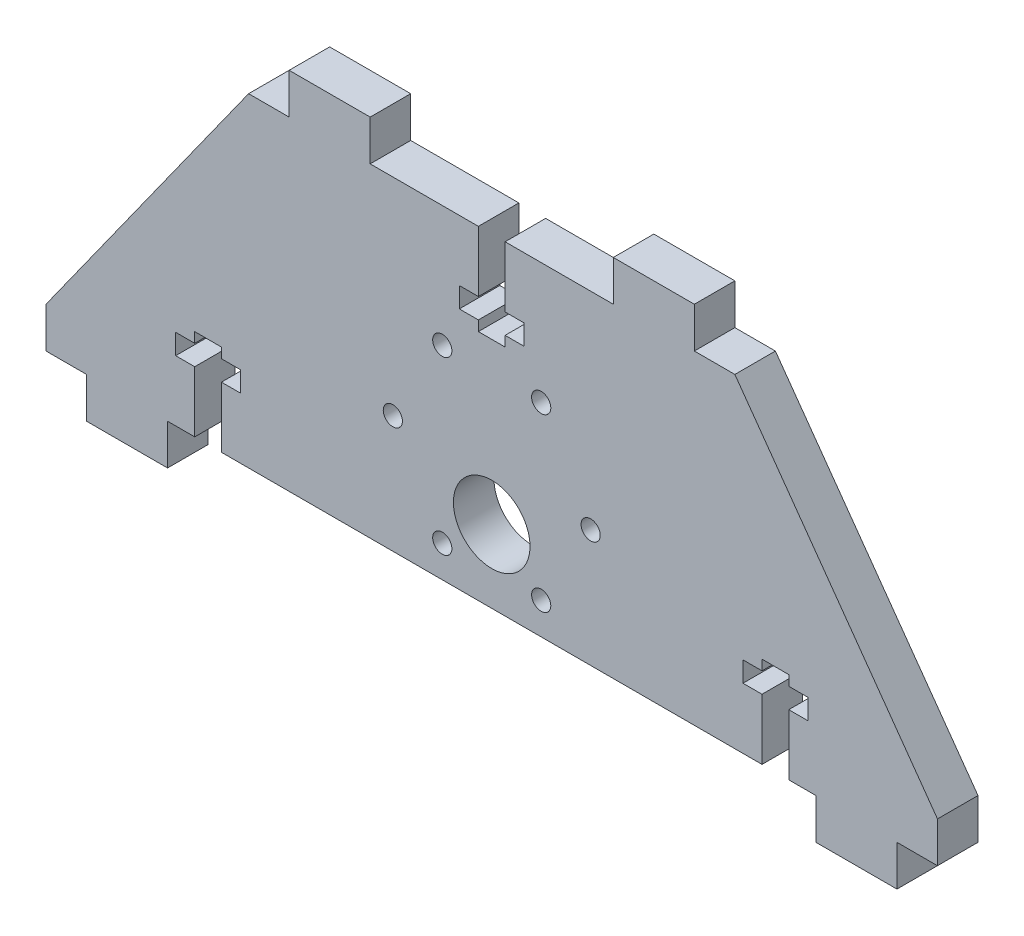
SolidWorks part; units mm, degrees
ref_plane "Front Plane" through (0, 0, 0) normal (0, 0, 1) x (1, 0, 0)
ref_plane "Top Plane" through (0, 0, 0) normal (0, 1, 0) x (1, 0, 0)
ref_plane "Right Plane" through (0, 0, 0) normal (1, 0, 0) x (0, 0, -1)
sketch "Sketch1" plane through (0, 0, 0) normal (0, 0, 1) x (1, 0, 0)
  line L1 (-69.85, 25.4) -> (69.85, 25.4)
  line L2 (-69.85, 25.4) -> (-69.85, -25.4)
  line L3 (-69.85, -25.4) -> (69.85, -25.4)
  line L4 (69.85, 25.4) -> (69.85, -25.4)
  line L5 (-69.85, 25.4) -> (69.85, -25.4) construction
  line L6 (-69.85, -25.4) -> (69.85, 25.4) construction
  point P0 (0, 0)
  dimension "D1" = 50.8
  dimension "D2" = 139.7
extrude "Boss-Extrude1" add sketch "Sketch1" along normal blind 6.35
sketch "Sketch2" plane through (0, 0, 0) normal (0, 0, -1) x (-1, 0, 0)
  line L0 (69.85, -25.4) -> (-69.85, -25.4) construction
  line L1 (-63.5, -25.4) -> (-50.8, -25.4)
  line L2 (-63.5, -25.4) -> (-63.5, -31.75)
  line L3 (-63.5, -31.75) -> (-50.8, -31.75)
  line L4 (-50.8, -25.4) -> (-50.8, -31.75)
  line L5 (-69.85, -25.4) -> (-69.85, 25.4) construction
  line L6 (-69.85, 25.4) -> (69.85, 25.4) construction
  line L7 (-31.75, 25.4) -> (-19.05, 25.4)
  line L8 (-31.75, 25.4) -> (-31.75, 31.75)
  line L9 (-31.75, 31.75) -> (-19.05, 31.75)
  line L10 (-19.05, 25.4) -> (-19.05, 31.75)
  dimension "D1" = 6.35
  dimension "D2" = 12.7
  dimension "D3" = 6.35
  dimension "D4" = 6.35
  dimension "D5" = 12.7
  dimension "D6" = 38.1
extrude "Boss-Extrude2" add sketch "Sketch2" against normal blind 6.35
sketch "Sketch3" plane through (0, 0, 0) normal (0, 0, -1) x (-1, 0, 0)
  line L1 (-46.5455, -25.4) -> (-46.5455, -15.875)
  line L2 (69.85, -25.4) -> (-50.8, -25.4) construction
  line L3 (-46.5455, -15.875) -> (-49.53, -15.875)
  line L4 (-49.53, -15.875) -> (-49.53, -12.7)
  line L5 (-49.53, -12.7) -> (-46.5455, -12.7)
  line L6 (-46.5455, -12.7) -> (-46.5455, -11.1125)
  line L7 (-46.5455, -11.1125) -> (-42.3545, -11.1125)
  line L8 (-44.45, -11.1125) -> (-44.45, -25.4) construction
  line L9 (-42.3545, -25.4) -> (-46.5455, -25.4)
  line L10 (-63.5, -31.75) -> (-50.8, -31.75) construction
  line L11 (-42.3545, -12.7) -> (-42.3545, -11.1125)
  line L12 (-39.37, -12.7) -> (-42.3545, -12.7)
  line L13 (-39.37, -15.875) -> (-39.37, -12.7)
  line L14 (-42.3545, -15.875) -> (-39.37, -15.875)
  line L15 (-42.3545, -25.4) -> (-42.3545, -15.875)
  line L16 (-50.8, -31.75) -> (-50.8, -25.4) construction
  dimension "D1" = 20.6375
  dimension "D2" = 1.5875
  dimension "D3" = 3.175
  dimension "D4" = 4.191
  dimension "D5" = 5.08
  dimension "D6" = 6.35
extrude "Cut-Extrude1" cut sketch "Sketch3" against normal blind 6.35
sketch "Sketch7" plane through (0, 0, 0) normal (0, 0, -1) x (-1, 0, 0)
  line L0 (-38.1, 25.4) -> (-69.85, -19.05)
  line L1 (-69.85, 25.4) -> (-31.75, 25.4) construction
  line L2 (-69.85, -25.4) -> (-69.85, 25.4) construction
  line L3 (-69.85, -19.05) -> (-69.85, 25.4)
  line L4 (-69.85, 25.4) -> (-38.1, 25.4)
  line L5 (-31.75, 31.75) -> (-31.75, 25.4) construction
  dimension "D1" = 6.35
  dimension "D2" = 6.35
extrude "Cut-Extrude8" cut sketch "Sketch7" against normal blind 6.35
mirror "Mirror2" about plane through (0, 0, 0) normal (1, 0, 0) of "Cut-Extrude8", "Boss-Extrude2"
mirror "Mirror4" about plane through (0, 0, 0) normal (1, 0, 0) of "Cut-Extrude1"
sketch "Sketch4" plane through (0, 0, 0) normal (0, 0, -1) x (-1, 0, 0)
  line L0 (0, 25.4) -> (0, 0) construction
  line L2 (2.0955, 25.4) -> (-2.0955, 25.4)
  line L3 (-2.0955, 25.4) -> (-2.0955, 15.875)
  line L4 (-2.0955, 15.875) -> (-5.08, 15.875)
  line L5 (-5.08, 15.875) -> (-5.08, 12.7)
  line L6 (-5.08, 12.7) -> (-2.0955, 12.7)
  line L7 (-2.0955, 12.7) -> (-2.0955, 11.1125)
  line L8 (-2.0955, 11.1125) -> (2.0955, 11.1125)
  line L10 (2.0955, 12.7) -> (2.0955, 11.1125)
  line L11 (5.08, 12.7) -> (2.0955, 12.7)
  line L12 (5.08, 15.875) -> (5.08, 12.7)
  line L13 (2.0955, 15.875) -> (5.08, 15.875)
  line L14 (2.0955, 25.4) -> (2.0955, 15.875)
  line L15 (-19.05, 31.75) -> (-31.75, 31.75) construction
  line L16 (-19.05, 25.4) -> (19.05, 25.4) construction
  point P15 (0, 11.1125)
  dimension "D1" = 2.0955
  dimension "D2" = 5.08
  dimension "D3" = 20.6375
  dimension "D4" = 1.5875
  dimension "D5" = 3.175
extrude "Cut-Extrude2" cut sketch "Sketch4" against normal blind 6.35
sketch "Sketch5" plane through (0, 0, 0) normal (0, 0, -1) x (-1, 0, 0)
  circle A0 centre (-7.75, 6.4234) radius 1.25 construction
  circle A1 centre (-15.5, -7) radius 1.25 construction
  circle A2 centre (-7.75, -20.4234) radius 1.25 construction
  circle A3 centre (7.75, -20.4234) radius 1.25 construction
  circle A4 centre (15.5, -7) radius 1.25 construction
  circle A5 centre (7.75, 6.4234) radius 1.25 construction
  circle A6 centre (-7.75, 6.4234) radius 1.25 construction
  circle A7 centre (-15.5, -7) radius 1.25 construction
  circle A8 centre (-7.75, -20.4234) radius 1.25 construction
  circle A9 centre (7.75, -20.4234) radius 1.25 construction
  circle A10 centre (15.5, -7) radius 1.25 construction
  circle A11 centre (7.75, 6.4234) radius 1.25 construction
  circle A12 centre (-7.75, 6.4234) radius 1.504
  circle A13 centre (-15.5, -7) radius 1.504
  circle A14 centre (-7.75, -20.4234) radius 1.504
  circle A15 centre (7.75, -20.4234) radius 1.504
  circle A16 centre (15.5, -7) radius 1.504
  circle A17 centre (7.75, 6.4234) radius 1.504
  dimension "D1" = 0.254
extrude "Cut-Extrude6" cut sketch "Sketch5" against normal blind 6.35
sketch "Sketch6" plane through (0, 0, 0) normal (0, 0, -1) x (-1, 0, 0)
  circle A0 centre (0, -14) radius 6 construction
  circle A1 centre (0, -14) radius 6
extrude "Cut-Extrude7" cut sketch "Sketch6" against normal blind 6.35
